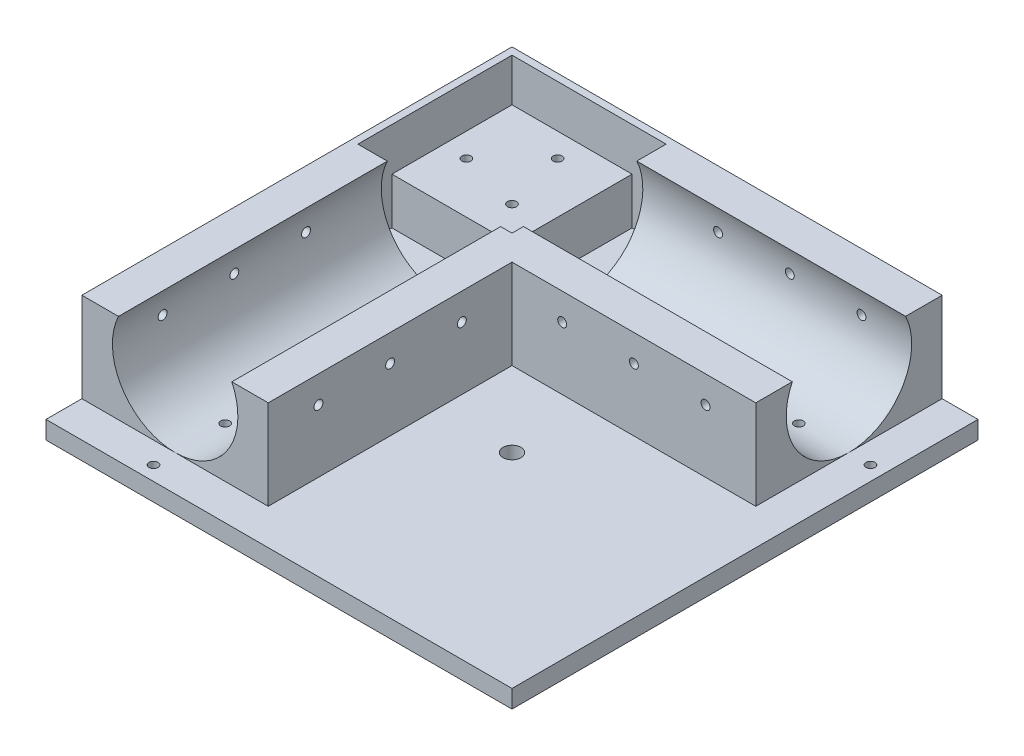
SolidWorks part; units mm, degrees
ref_plane "Front" through (0, 0, 0) normal (0, 0, 1) x (1, 0, 0)
ref_plane "Top" through (0, 0, 0) normal (0, 1, 0) x (1, 0, 0)
ref_plane "Right" through (0, 0, 0) normal (1, 0, 0) x (0, 0, -1)
sketch "草图1" plane through (0, 0, 0) normal (0, 1, 0) x (1, 0, 0)
  line L1 (0, 0) -> (130, 0)
  line L2 (0, 0) -> (0, 130)
  line L3 (0, 130) -> (130, 130)
  line L4 (130, 0) -> (130, 130)
  dimension "D1" = 130
  dimension "D2" = 130
extrude "底板" add sketch "草图1" along normal blind 5
sketch "草图2" plane through (0, 5, 0) normal (0, 1, 0) x (1, 0, 0)
  line L1 (0, 0) -> (52, 0)
  line L2 (0, 0) -> (0, 85)
  line L3 (0, 85) -> (52, 85)
  line L4 (52, 0) -> (52, 85)
  line L22 (130, 130) -> (45, 130)
  line L23 (130, 130) -> (130, 78)
  line L24 (130, 78) -> (45, 78)
  line L25 (45, 130) -> (45, 78)
  dimension "D1" = 85
  dimension "D2" = 52
  dimension "D5" = 85
  dimension "D6" = 52
extrude "物镜底座" add sketch "草图2" along normal blind 25 contours L3 L25 L24 L4
sketch "草图3" plane through (0, 0, 0) normal (0, 0, 1) x (1, 0, 0)
  line L1 (52, 5) -> (0, 5) construction
  line L2 (0, 30) -> (0, 0) construction
  line L3 (26.0277, 22.5) -> (26, 5) construction
  circle A0 centre (26.0277, 22.5) radius 17.5
  dimension "D1" = 17.5
  dimension "D2" = 35
extrude "物镜1" cut sketch "草图3" against normal up to surface (85 mm away) up to face at (22.5, 17.5, -85)
sketch "草图4" plane through (130, 0, 0) normal (1, 0, 0) x (0, 0, -1)
  line L0 (78, 5) -> (130, 5) construction
  line L3 (130, 30) -> (130, 0) construction
  circle A0 centre (104, 22.5) radius 17.5
extrude "物镜2" cut sketch "草图4" against normal up to surface (85 mm away) up to face at (45, 17.5, -107.5)
sketch "草图8" plane through (130, 0, 0) normal (1, 0, 0) x (0, 0, -1)
  line L1 (78, 5) -> (130, 5)
  line L2 (78, 5) -> (78, 30)
  line L3 (78, 30) -> (130, 30)
  line L4 (130, 5) -> (130, 30)
extrude "物镜底座切除1" cut sketch "草图8" against normal blind 10
sketch "草图9" plane through (0, 0, 0) normal (0, 0, 1) x (1, 0, 0)
  line L1 (52, 5) -> (0, 5)
  line L2 (52, 5) -> (52, 30)
  line L3 (52, 30) -> (0, 30)
  line L4 (0, 5) -> (0, 30)
extrude "物镜底座切除2" cut sketch "草图9" against normal blind 10
sketch "草图5" plane through (0, 5, 0) normal (0, 1, 0) x (1, 0, 0)
  line L0 (45, 130) -> (45, 104) construction
  line L1 (0, 130) -> (45, 130)
  line L2 (0, 130) -> (0, 128)
  line L3 (0, 128) -> (45, 128)
  line L4 (45, 130) -> (45, 128)
  line L6 (0, 85) -> (2, 85)
  line L7 (0, 85) -> (0, 130)
  line L8 (0, 130) -> (2, 130)
  line L9 (2, 85) -> (2, 130)
  line M3 (0, 130) -> (0, 85)
  line M4 (0, 85) -> (26.0277, 85)
  line M7 (45, 104) -> (45, 130)
  line M8 (45, 130) -> (0, 130)
  dimension "D1" = 2
  dimension "D2" = 2
extrude "边壳" add sketch "草图5" along normal blind 25 contours L3 L9 L1 M3 | L9 L3 M4 M3 | L9 L3 M7 M8
sketch "草图7" plane through (0, 5, 0) normal (0, 1, 0) x (1, 0, 0)
  line L5 (2, 128) -> (35.5, 128)
  line L6 (2, 128) -> (2, 94.5)
  line L7 (2, 94.5) -> (35.5, 94.5)
  line L8 (35.5, 128) -> (35.5, 94.5)
  dimension "D1" = 33.5
  dimension "D2" = 33.5
extrude "载物台" add sketch "草图7" along normal blind 13
hole_wizard "底部固定孔" positions "3D草图1" profile "草图11" tap size "M6" standard "GB"
sketch3d "3D草图1"
  point P0 (48, 0, -82)
  point P3 (73, 0, -57)
  dimension "D1" = 48
  dimension "D2" = 48
  dimension "D3" = 73
  dimension "D4" = 73
sketch "草图11" plane through (48, 0, -82) normal (1, 0, 0) x (0, 0, -1)
  line L0 (0, 0) -> (0, 6.5022)
  line L1 (0, 6.5022) -> (2.5, 5)
  line L2 (2.5, 5) -> (2.5, 0)
  line L5 (2.5, 0) -> (0, 0)
  line L10 (0, 6.5022) -> (-2.5, 5) construction
  line L11 (0, -6.35) -> (0, 107.95) construction
  dimension "螺纹孔钻头直径" = 5
  dimension "螺纹孔钻头深度" = 5
  dimension "导头角度" = 118
cosmetic thread "孔螺蚊线1" parameters "D1"=12, "D2"=6
cosmetic thread "孔螺蚊线2" parameters "D1"=12, "D2"=6
sketch "光心图" plane through (0, 5, 0) normal (0, 1, 0) x (1, 0, 0)
  line L0 (0, 10) -> (52, 10) construction
  line L1 (26.0277, 10) -> (26.0277, 85)
  line L2 (120, 104) -> (45, 104)
  line L3 (45, 104) -> (26.0277, 104)
  line L4 (26.0277, 104) -> (26.0277, 85)
  line L5 (120, 130) -> (0, 130) construction
  line L6 (26.0277, 104) -> (120, 104)
  line L7 (26.0277, 104) -> (26.0277, 10)
  point P14 (26.0277, 104)
  dimension "D1" = 26
hole_wizard "物镜1底孔" positions "草图19" profile "草图20" tap size "M3" standard "GB" end condition up to next
sketch "草图19" plane through (0, 0, 0) normal (0, -1, 0) x (-1, 0, 0)
  line L0 (0, 130) -> (0, 0) construction
  line L1 (-130, 130) -> (0, 130) construction
  line L3 (-26, 79.6501) -> (-26, 64)
  line L4 (-26, 64) -> (-26, 2.1943)
  point P0 (-26, 64)
  point P7 (-26, 79)
  point P18 (-26, 44)
  point P20 (-26, 24)
  point P22 (-26, 4)
  dimension "D1" = 26
  dimension "D2" = 66
  dimension "D3" = 15
  dimension "D4" = 26
  dimension "D5" = 20
  dimension "D6" = 20
  dimension "D7" = 20
sketch "草图20" plane through (26, 0, -64) normal (1, 0, 0) x (0, 0, -1)
  line L0 (0, 0) -> (0, 5)
  line L1 (0, 5) -> (1.25, 5)
  line L2 (1.25, 5) -> (1.25, 0)
  line L5 (1.25, 0) -> (0, 0)
  line L11 (0, -6.35) -> (0, 107.95) construction
  dimension "通孔螺纹孔钻头直径" = 2.5
  dimension "通孔螺纹孔钻头深度" = 5
cosmetic thread "孔螺蚊线9" parameters "D2"=3
cosmetic thread "孔螺蚊线10" parameters "D2"=3
cosmetic thread "孔螺蚊线11" parameters "D2"=3
cosmetic thread "孔螺蚊线12" parameters "D2"=3
cosmetic thread "孔螺蚊线13" parameters "D2"=3
hole_wizard "物镜2底孔" positions "草图21" profile "草图22" tap size "M3" standard "GB" end condition up to next
sketch "草图21" plane through (0, 0, 0) normal (0, -1, 0) x (-1, 0, 0)
  line L0 (-130, 130) -> (0, 130) construction
  line L1 (0, 130) -> (0, 0) construction
  point P0 (-66, 104)
  point P2 (-66, 104)
  point P9 (-51, 104)
  point P11 (-86, 104)
  point P13 (-106, 104)
  point P15 (-126, 104)
  dimension "D1" = 26
  dimension "D2" = 66
  dimension "D3" = 15
  dimension "D4" = 20
  dimension "D5" = 20
  dimension "D6" = 20
sketch "草图22" plane through (66, 0, -104) normal (1, 0, 0) x (0, 0, -1)
  line L0 (0, 0) -> (0, 5)
  line L1 (0, 5) -> (1.25, 5)
  line L2 (1.25, 5) -> (1.25, 0)
  line L5 (1.25, 0) -> (0, 0)
  line L11 (0, -6.35) -> (0, 107.95) construction
  dimension "通孔螺纹孔钻头直径" = 2.5
  dimension "通孔螺纹孔钻头深度" = 5
cosmetic thread "孔螺蚊线14" parameters "D2"=3
cosmetic thread "孔螺蚊线15" parameters "D2"=3
cosmetic thread "孔螺蚊线16" parameters "D2"=3
cosmetic thread "孔螺蚊线17" parameters "D2"=3
cosmetic thread "孔螺蚊线18" parameters "D2"=3
cosmetic thread "孔螺蚊线19" parameters "D2"=3
sketch "载物台螺丝草图" plane through (0, 18, 0) normal (0, 1, 0) x (1, 0, 0)
  line L0 (2, 128) -> (35.5, 94.5)
  line L4 (0, 10) -> (0, 130) construction
  line L5 (26, 104) -> (21.3413, 121.3867)
  line L6 (21.3413, 121.3867) -> (8.6133, 108.6587)
  line L7 (8.6133, 108.6587) -> (26, 104)
  point P4 (26, 104)
  dimension "D1" = 26
  dimension "D2" = 18
  dimension "D3" = 18
  dimension "D4" = 18
  dimension "D5" = 9
hole_wizard "载物台螺丝孔" positions "草图25" profile "草图26" tap size "M3" standard "GB" end condition up to next
sketch "草图25" plane through (0, 18, 0) normal (0, 1, 0) x (1, 0, 0)
  point P0 (21.3413, 121.3867)
  point P3 (8.6133, 108.6587)
  point P6 (26, 104)
sketch "草图26" plane through (21.3413, 18, -121.3867) normal (1, 0, 0) x (0, 0, 1)
  line L0 (0, 0) -> (0, 18)
  line L1 (0, 18) -> (1.25, 18)
  line L2 (1.25, 18) -> (1.25, 0)
  line L5 (1.25, 0) -> (0, 0)
  line L11 (0, -6.35) -> (0, 107.95) construction
  dimension "通孔螺纹孔钻头直径" = 2.5
  dimension "通孔螺纹孔钻头深度" = 18
cosmetic thread "孔螺蚊线20" parameters "D2"=3
cosmetic thread "孔螺蚊线21" parameters "D2"=3
cosmetic thread "孔螺蚊线22" parameters "D2"=3
hole_wizard "物镜1侧孔" positions "草图27" profile "草图28" tap size "M3" standard "GB" end condition through all
sketch "草图27" plane through (52, 0, 0) normal (1, 0, 0) x (0, 0, -1)
  line L0 (10, 5) -> (78, 5) construction
  line L1 (130, 30) -> (130, 0) construction
  point P0 (44, 22.5)
  point P2 (24, 22.5)
  point P9 (64, 22.5)
  dimension "D1" = 17.5
  dimension "D2" = 17.5
  dimension "D3" = 86
  dimension "D4" = 20
  dimension "D5" = 20
sketch "草图28" plane through (52, 22.5, -44) normal (0, 1, 0) x (0, 0, -1)
  line L0 (0, 0) -> (0, 52)
  line L1 (0, 52) -> (1.25, 52)
  line L2 (1.25, 52) -> (1.25, 0)
  line L5 (1.25, 0) -> (0, 0)
  line L11 (0, -6.35) -> (0, 107.95) construction
  dimension "通孔螺纹孔钻头直径" = 2.5
  dimension "通孔螺纹孔钻头深度" = 52
cosmetic thread "孔螺蚊线23" parameters "D2"=3
cosmetic thread "孔螺蚊线24" parameters "D2"=3
cosmetic thread "孔螺蚊线27" parameters "D2"=3
hole_wizard "物镜2侧孔" positions "草图29" profile "草图30" tap size "M3" standard "GB" end condition through all
sketch "草图29" plane through (0, 0, -78) normal (0, 0, 1) x (1, 0, 0)
  line L0 (120, 5) -> (52, 5) construction
  line L1 (0, 30) -> (0, 5) construction
  point P0 (86, 22.5)
  point P2 (106, 22.5)
  point P9 (66, 22.5)
  dimension "D1" = 17.5
  dimension "D2" = 17.5
  dimension "D3" = 86
  dimension "D4" = 20
  dimension "D5" = 20
sketch "草图30" plane through (86, 22.5, -78) normal (1, 0, 0) x (0, -1, 0)
  line L0 (0, 0) -> (0, 52)
  line L1 (0, 52) -> (1.25, 52)
  line L2 (1.25, 52) -> (1.25, 0)
  line L5 (1.25, 0) -> (0, 0)
  line L11 (0, -6.35) -> (0, 107.95) construction
  dimension "通孔螺纹孔钻头直径" = 2.5
  dimension "通孔螺纹孔钻头深度" = 52
cosmetic thread "孔螺蚊线25" parameters "D2"=3
cosmetic thread "孔螺蚊线26" parameters "D2"=3
cosmetic thread "孔螺蚊线28" parameters "D2"=3
sketch "原点图" plane through (0, 5, 0) normal (0, 1, 0) x (1, 0, 0)
  line L0 (0, 0) -> (130, 0) construction
  line L1 (130, 0) -> (130, 130) construction
  circle A0 centre (26, 104) radius 1.25 construction
  circle A1 centre (21.3413, 121.3867) radius 1.25 construction
  circle A2 centre (8.6133, 108.6587) radius 1.25 construction
  circle A3 centre (26, 79) radius 1.25 construction
  circle A5 centre (26, 44) radius 1.25 construction
  circle A6 centre (26, 24) radius 1.25 construction
  circle A7 centre (26, 4) radius 1.25 construction
  circle A8 centre (73, 57) radius 2.5 construction
  circle A9 centre (48, 82) radius 2.5 construction
  point P4 (65, 65)
  dimension "D8" = 39
  dimension "D21" = 17
  dimension "D1" = 65
  dimension "D2" = 65
  dimension "D3" = 20
  dimension "D4" = 55
  dimension "D5" = 13
  dimension "D6" = 55
  dimension "D7" = 13
  dimension "D9" = 39
  dimension "D10" = 43.6587
  dimension "D11" = 56.3867
  dimension "D12" = 56.3867
  dimension "D13" = 43.6587
  dimension "D14" = 63
  dimension "D15" = 29.5
  dimension "D16" = 14
  dimension "D17" = 21
  dimension "D18" = 41
  dimension "D19" = 61
  dimension "D20" = 8
sketch "草图31" plane through (0, 5, 0) normal (0, 1, 0) x (1, 0, 0)
  line L0 (45, 85) -> (2, 128) construction
  line L1 (35.5, 128) -> (2, 94.5)
  point P8 (23.5, 106.5)
  point P10 (18.75, 111.25)
  dimension "D1" = 41.5
  dimension "D2" = 46.25
equation "\"D2@草图5\"=\"D1@草图5\""
equation "\"D5@草图2\"=\"D1@草图2\""
equation "\"D6@草图2\"=\"D2@草图2\""
equation "\"D2@草图7\"=\"D1@草图7\""
equation "\"D2@草图27\"=\"D1@草图27\""
